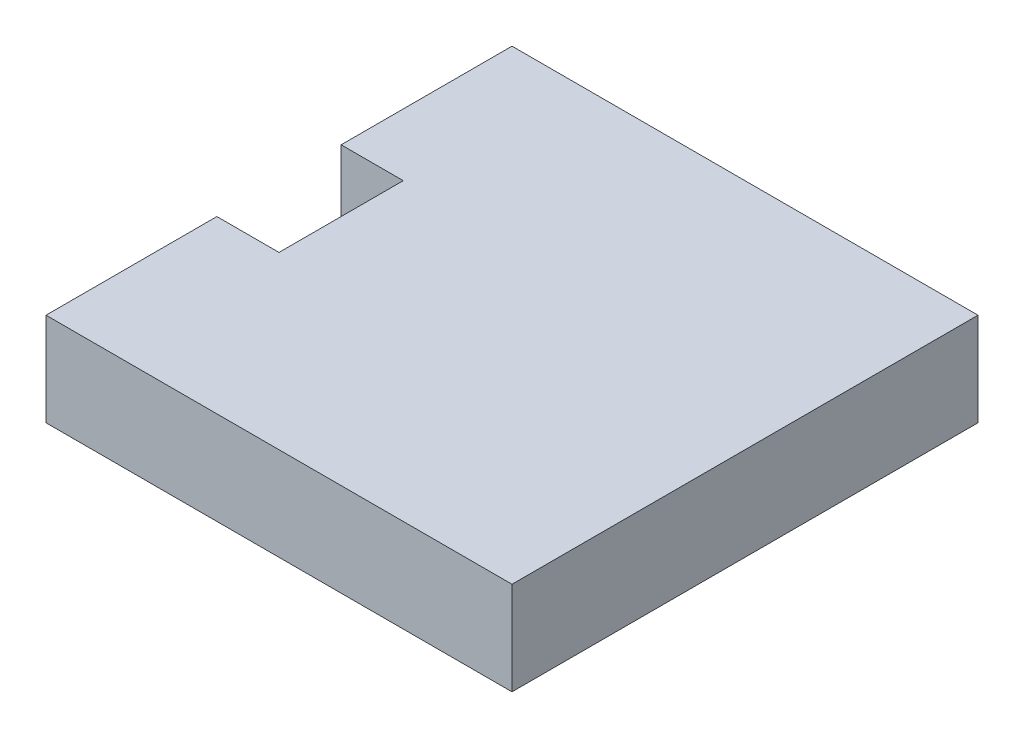
SolidWorks part; units mm, degrees
ref_plane "Front Plane" through (0, 0, 0) normal (0, 0, 1) x (1, 0, 0)
ref_plane "Top Plane" through (0, 0, 0) normal (0, 1, 0) x (1, 0, 0)
ref_plane "Right Plane" through (0, 0, 0) normal (1, 0, 0) x (0, 0, -1)
sketch "Sketch1" plane through (0, 0, 0) normal (0, 1, 0) x (1, 0, 0)
  line L1 (0, 1.5) -> (-1.5, 1.5)
  line L7 (-1.5, 0) -> (0, 0)
  line L8 (0, 1.5) -> (0, 0)
  line L9 (-1.5, 1.5) -> (-1.5, 0.95)
  line L10 (-1.5, 0.95) -> (-1.3, 0.95)
  line L11 (-1.3, 0.95) -> (-1.3, 0.55)
  line L12 (-1.3, 0.55) -> (-1.5, 0.55)
  line L13 (-1.5, 0.55) -> (-1.5, 0)
  point P3 (-1.3, 0.75)
  point P10 (0, 0.75)
  dimension "D1" = 1.5
  dimension "D2" = 1.5
  dimension "D3" = 0.4
  dimension "D4" = 0.2
extrude "Boss-Extrude1" add sketch "Sketch1" along normal blind 0.3
equation "\"t\"= 0.3'thickness of the sheets"
equation "\"FlexJoint\"= 0.15'Width of flextures"
equation "\"FoldJoint\"= 0.4'Width of folding joints"
equation "\"AssembleAngle\"= 90'Angle of assembly parts"
equation "\"D1@Boss-Extrude1\"=\"t\""
